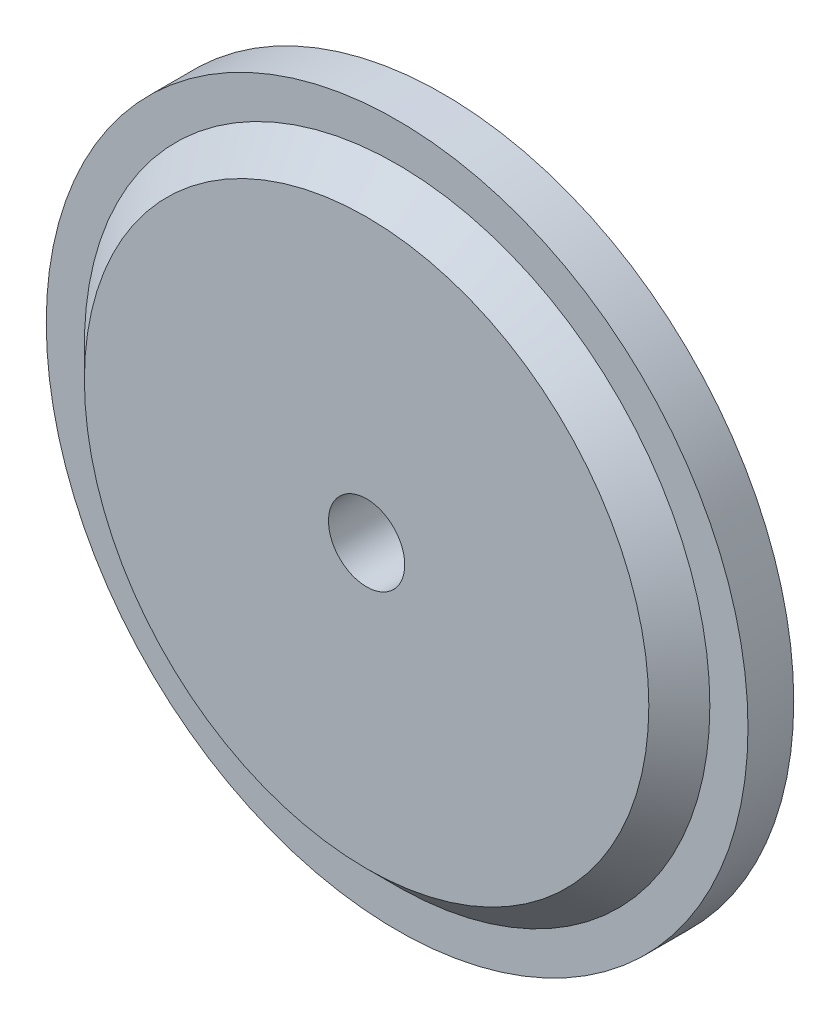
SolidWorks part; units mm, degrees
material "6061-T6 (SS)"
ref_plane "Front Plane" through (0, 0, 0) normal (0, 0, 1) x (1, 0, 0)
ref_plane "Top Plane" through (0, 0, 0) normal (0, 1, 0) x (1, 0, 0)
ref_plane "Right Plane" through (0, 0, 0) normal (1, 0, 0) x (0, 0, -1)
sketch "Sketch1" plane through (0, 0, 0) normal (0, 0, 1) x (1, 0, 0)
  circle A0 centre (0, 0) radius 29.21
  circle A1 centre (0, 0) radius 3.175
  dimension "D1" = 6.35
  dimension "D2" = 58.42
extrude "Boss-Extrude1" add sketch "Sketch1" along normal blind 6.35
sketch "Sketch2" plane through (0, 0, 0) normal (1, 0, 0) x (0, 0, -1)
  line L0 (-6.35, 29.21) -> (-3.81, 29.21)
  line L2 (0, 29.21) -> (-6.35, 29.21) construction
  line L4 (-3.81, 29.21) -> (-3.81, 26.035)
  line L5 (-3.81, 26.035) -> (-6.35, 23.495)
  line L6 (-6.35, 29.21) -> (-6.35, -29.21) construction
  line L7 (-6.35, 23.495) -> (-6.35, 29.21)
  line L8 (0, 0) -> (-6.35, 0) construction
  dimension "D1" = 2.54
  dimension "D2" = 135
  dimension "D3" = 26.035
revolve "Cut-Revolve1" cut sketch "Sketch2" angle 360 about axis through (0, 0, 6.35) along (0, 0, -1)
